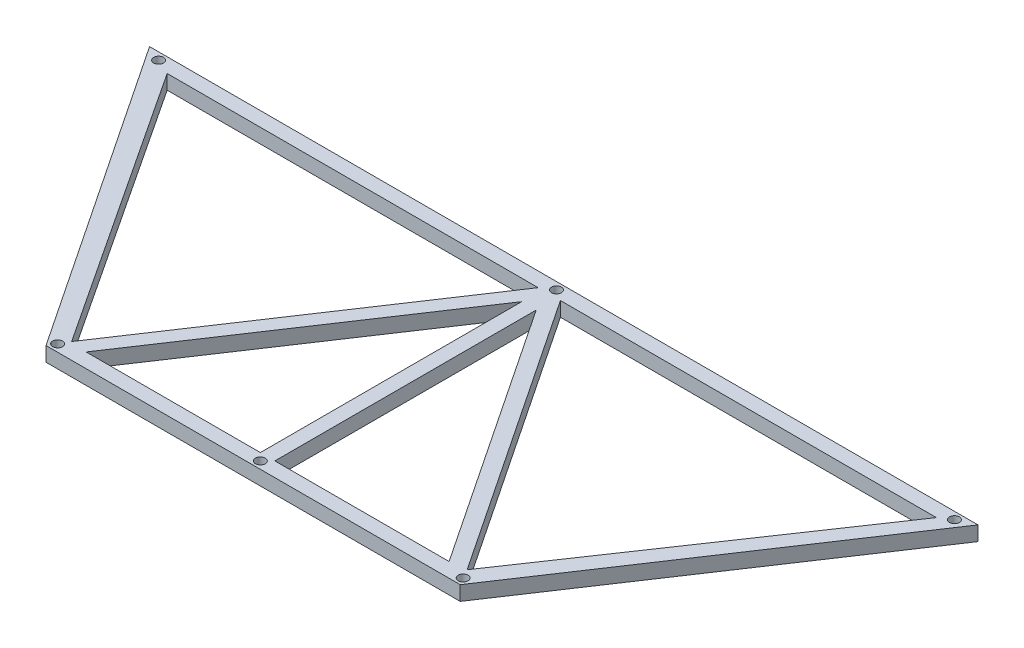
SolidWorks part; units mm, degrees
material "AISI 1020"
ref_plane "Front Plane" through (0, 0, 0) normal (0, 0, 1) x (1, 0, 0)
ref_plane "Top Plane" through (0, 0, 0) normal (0, 1, 0) x (1, 0, 0)
ref_plane "Right Plane" through (0, 0, 0) normal (1, 0, 0) x (0, 0, -1)
sketch "Sketch1" plane through (0, 0, 0) normal (0, 1, 0) x (1, 0, 0)
  line L1 (0, -55) -> (0, 55) construction
  line L2 (0, 300) -> (400, 300)
  line L3 (400, 300) -> (200, 0)
  line L4 (-55, 0) -> (55, 0) construction
  line L5 (200, 0) -> (0, 0)
  line L6 (7, 14) -> (7, 266.3806)
  line L7 (10.7463, 286) -> (373.8408, 286)
  line L8 (373.8408, 286) -> (190.836, 15.8654)
  line L9 (175.2537, 14) -> (7, 14)
  line L19 (175.2537, 14) -> (7, 266.3806)
  line L20 (0, 132.2609) -> (0, -97.8076) construction
  line L21 (190.836, 15.8654) -> (10.7463, 286)
  line L26 (-190.9474, 15.6984) -> (-10.7463, 286)
  line L30 (-175.2537, 14) -> (-7, 266.3806)
  line L34 (-175.2537, 14) -> (-7, 14)
  line L35 (-368.9946, 286) -> (-190.9474, 15.6984)
  line L36 (-10.7463, 286) -> (-368.9946, 286)
  line L37 (-7, 14) -> (-7, 266.3806)
  line L38 (-200, 0) -> (0, 0)
  line L39 (-400, 300) -> (-200, 0)
  line L40 (0, 300) -> (-400, 300)
  circle A0 centre (0, 293) radius 4.7625
  circle A1 centre (0, 7) radius 4.7625
  circle A2 centre (384.259, 293) radius 4.7625
  circle A3 centre (-384.259, 293) radius 4.7625
  circle A4 centre (-195.7935, 7) radius 4.7625
  circle A5 centre (195.7935, 7) radius 4.7625
  dimension "D5" = 9.525
  dimension "D7" = 9.525
  dimension "D9" = 9.525
  dimension "D10" = 9.525
  dimension "D1" = 400
  dimension "D2" = 200
  dimension "D3" = 300
  dimension "D4" = 14
  dimension "D6" = 7
  dimension "D8" = 7
  dimension "D11" = 7
  dimension "D12" = 7
  dimension "D13" = 14
  dimension "D14" = 14
  dimension "D15" = 14
extrude "Boss-Extrude2" add sketch "Sketch1" along normal blind 14
